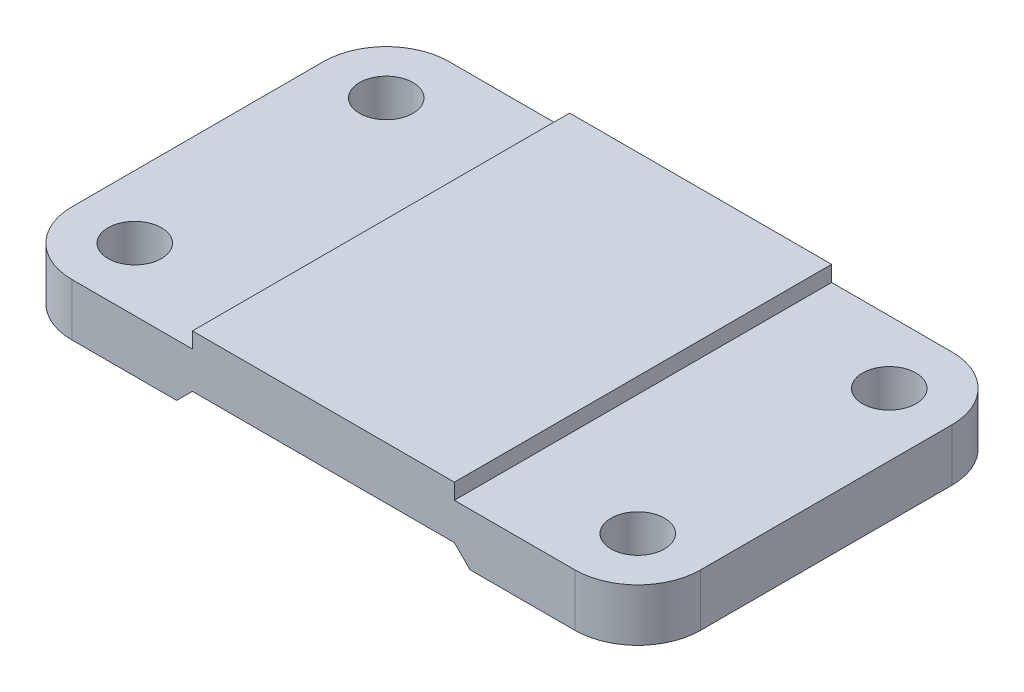
SolidWorks part; units mm, degrees
ref_plane "Front Plane" through (0, 0, 0) normal (0, 0, 1) x (1, 0, 0)
ref_plane "Top Plane" through (0, 0, 0) normal (0, 1, 0) x (1, 0, 0)
ref_plane "Right Plane" through (0, 0, 0) normal (1, 0, 0) x (0, 0, -1)
sketch "Sketch2" plane through (0, 0, 0) normal (0, 0, 1) x (1, 0, 0)
  line L0 (0, 0) -> (0, 10)
  line L1 (0, 10) -> (35, 10)
  line L2 (35, 10) -> (35, 13)
  line L3 (35, 13) -> (85, 13)
  line L4 (85, 13) -> (85, 10)
  line L5 (85, 10) -> (120, 10)
  line L6 (120, 10) -> (120, 0)
  line L7 (120, 0) -> (88, 0)
  line L11 (32, 0) -> (0, 0)
  line L14 (32, 0) -> (35, 3)
  line L15 (35, 3) -> (85, 3)
  line L16 (85, 3) -> (88, 0)
  point P7 (60, 13)
  point P11 (60, 3)
  dimension "D1" = 10
  dimension "D2" = 3
  dimension "D3" = 50
  dimension "D4" = 56
  dimension "D5" = 120
  dimension "D6" = 60
  dimension "D7" = 45
  dimension "D8" = 45
  dimension "D9" = 3
extrude "Boss-Extrude2" add sketch "Sketch2" along normal blind 72 contours L3 L4 L5 L6 L7 L16 L15 L14 L11 L0 L1 L2
fillet "Fillet1" radius 12 4 edges at (0, 5, 0) (0, 5, 72) (120, 5, 0) (120, 5, 72)
sketch "Sketch3" plane through (0, 0, 0) normal (0, 1, 0) x (1, 0, 0)
  line L0 (60, 0) -> (60, -72) construction
  line L1 (35, 0) -> (85, 0) construction
  line L2 (35, -72) -> (85, -72) construction
  circle A0 centre (12, -12) radius 5.1
  circle A1 centre (12, -60) radius 5.1
  arc A2 (0, -60) -> (12, -72) centre (12, -60) ccw construction
  arc A3 (12, 0) -> (0, -12) centre (12, -12) ccw construction
  circle A4 centre (108, -60) radius 5.1
  circle A5 centre (108, -12) radius 5.1
  dimension "D1" = 10.2
extrude "Cut-Extrude1" cut sketch "Sketch3" along normal through all
